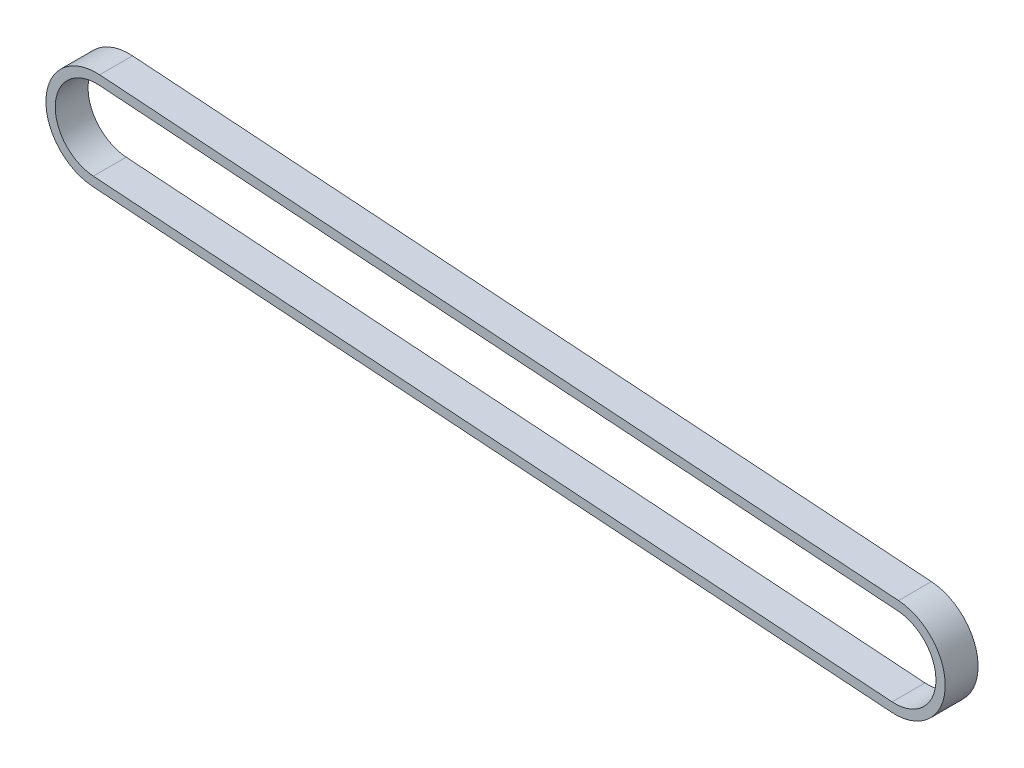
SolidWorks part; units mm, degrees
ref_plane "Front Plane" through (0, 0, 0) normal (0, 0, 1) x (1, 0, 0)
ref_plane "Top Plane" through (0, 0, 0) normal (0, 1, 0) x (1, 0, 0)
ref_plane "Right Plane" through (0, 0, 0) normal (1, 0, 0) x (0, 0, -1)
sketch "Sketch1" plane through (0, 0, 0) normal (0, 0, 1) x (1, 0, 0)
  line L0 (0, 0) -> (218.7346, -15.3045) construction
  line L1 (0, 0) -> (218.7346, -15.3045) construction
  line L2 (0.7826, 11.1851) -> (219.5172, -4.1194)
  line L3 (-0.7826, -11.1851) -> (217.952, -26.4895)
  arc A1 (0.7826, 11.1851) -> (-0.7826, -11.1851) centre (0, 0) ccw
  arc A3 (217.952, -26.4895) -> (219.5172, -4.1194) centre (218.7346, -15.3045) ccw
  point P1 (109.3673, -7.6522)
extrude "Extrude-Thin2" add sketch "Sketch1" along normal blind 9 thin thin type one direction wall 2.54
